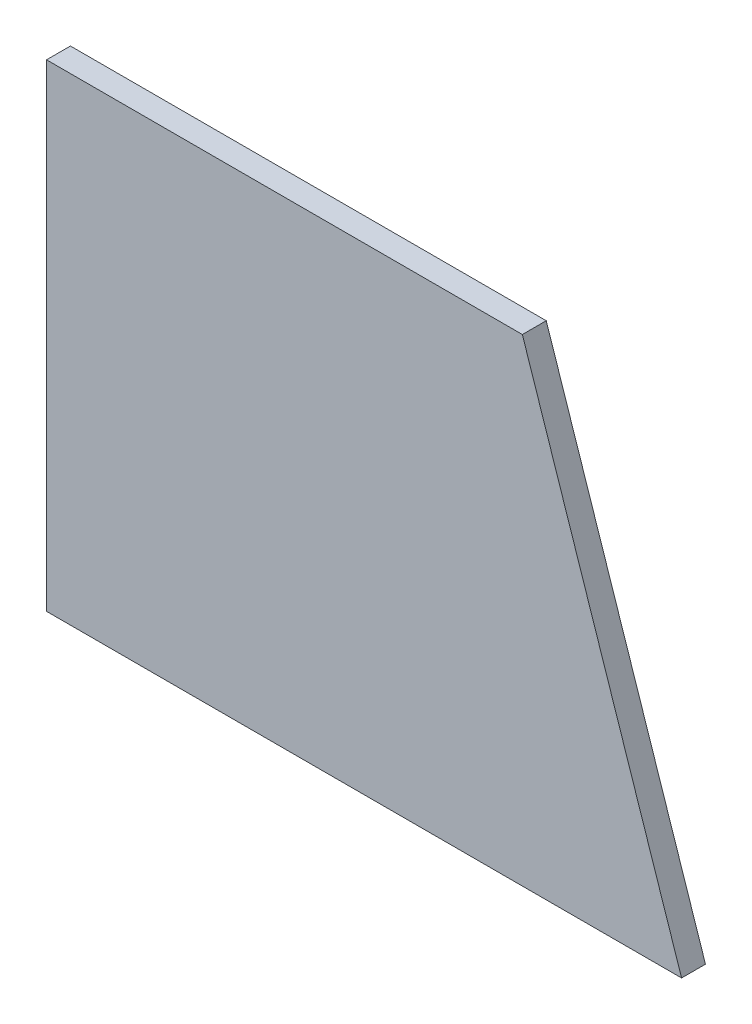
SolidWorks part; units mm, degrees
ref_plane "Front Plane" through (0, 0, 0) normal (0, 0, 1) x (1, 0, 0)
ref_plane "Top Plane" through (0, 0, 0) normal (0, 1, 0) x (1, 0, 0)
ref_plane "Right Plane" through (0, 0, 0) normal (1, 0, 0) x (0, 0, -1)
sketch "Sketch2" plane through (0, 0, 0) normal (0, 0, 1) x (1, 0, 0)
  line L0 (0, 0.35) -> (0.2977, 0.35)
  line L2 (0.2977, 0.35) -> (0.4977, -0.25)
  line L3 (0.4977, -0.25) -> (-0.3, -0.25)
  line L4 (-0.3, -0.25) -> (-0.3, 0.35)
  line L5 (-0.3, 0.35) -> (0, 0.35)
  dimension "D1" = 0.35
  dimension "D3" = 0.6
extrude "Boss-Extrude1" add sketch "Sketch2" along normal mid plane 0.03
